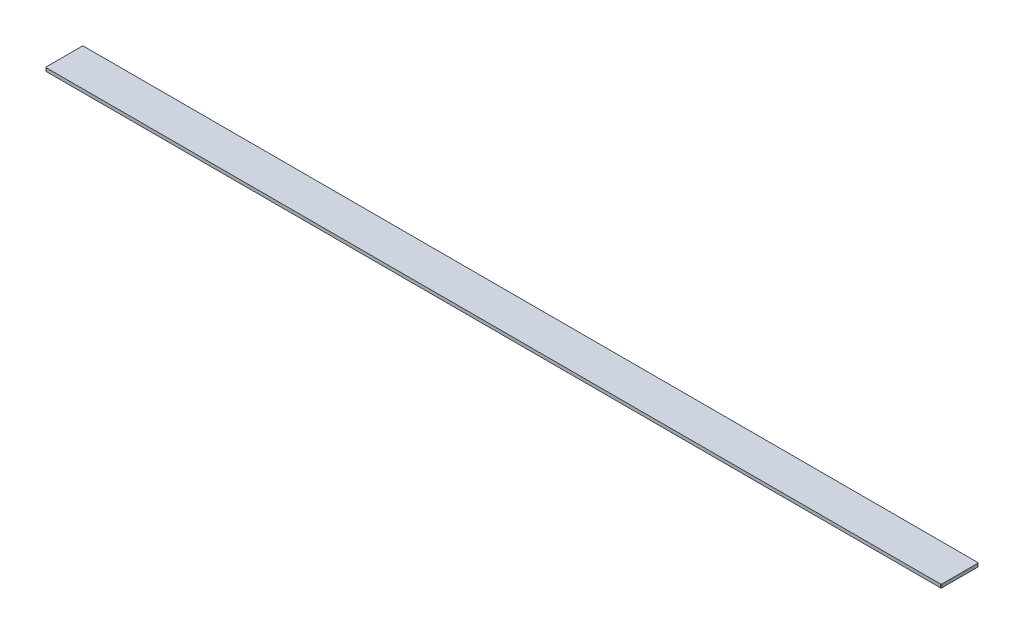
SolidWorks part; units mm, degrees
ref_plane "Front Plane" through (0, 0, 0) normal (0, 0, 1) x (1, 0, 0)
ref_plane "Top Plane" through (0, 0, 0) normal (0, 1, 0) x (1, 0, 0)
ref_plane "Right Plane" through (0, 0, 0) normal (1, 0, 0) x (0, 0, -1)
sketch "Sketch1" plane through (0, 0, 0) normal (0, 1, 0) x (1, 0, 0)
  line L1 (270, -11.25) -> (-270, -11.25)
  line L2 (270, -11.25) -> (270, 11.25)
  line L3 (270, 11.25) -> (-270, 11.25)
  line L4 (-270, -11.25) -> (-270, 11.25)
  line L5 (270, -11.25) -> (-270, 11.25) construction
  line L6 (270, 11.25) -> (-270, -11.25) construction
  point P0 (0, 0)
  dimension "D1" = 22.5
  dimension "D2" = 540
extrude "Boss-Extrude1" add sketch "Sketch1" along normal blind 2
fillet "Fillet1" radius 0.5 4 edges at (-270, 1, -11.25) (270, 1, -11.25) (270, 1, 11.25) (-270, 1, 11.25)
